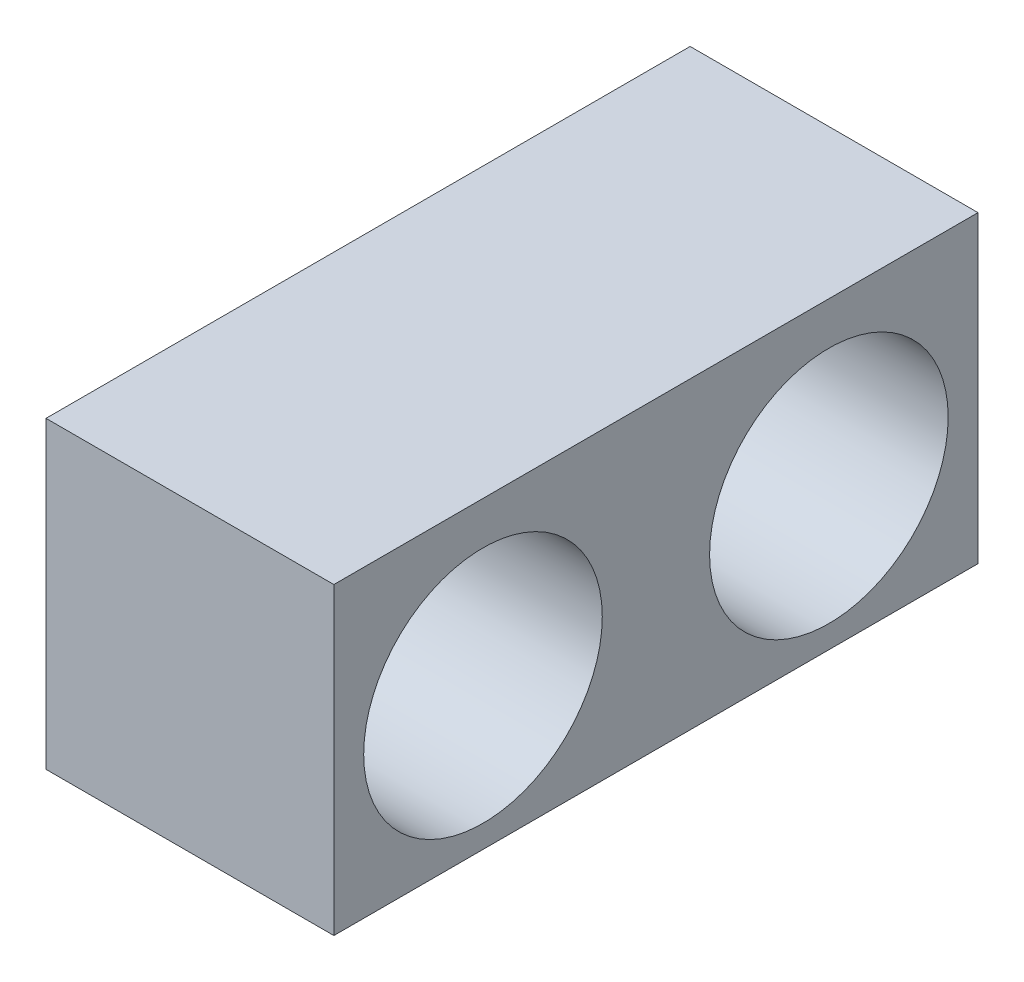
SolidWorks part; units mm, degrees
ref_plane "Front Plane" through (0, 0, 0) normal (0, 0, 1) x (1, 0, 0)
ref_plane "Top Plane" through (0, 0, 0) normal (0, 1, 0) x (1, 0, 0)
ref_plane "Right Plane" through (0, 0, 0) normal (1, 0, 0) x (0, 0, -1)
other "Lead Shot"
sketch "Sketch1" plane through (0, 0, 0) normal (0, 1, 0) x (1, 0, 0)
  circle A0 centre (0, 0) radius 75
  dimension "D1" = 150
extrude "Boss-Extrude1" add sketch "Sketch1" along normal blind 100
sketch "Sketch2" plane through (0, 100, 0) normal (0, 1, 0) x (1, 0, 0)
  line L1 (-22.2, -49.6757) -> (-22.2, 49.6757) construction
  line L3 (-22.2, -49.6757) -> (-22.2, 49.6757)
  line L4 (22.2, 49.6757) -> (22.2, -49.6757) construction
  line L5 (22.2, 49.6757) -> (22.2, -49.6757)
  line L6 (-22.2, -49.6757) -> (22.2, -49.6757)
  line L7 (-22.2, 49.6757) -> (22.2, 49.6757)
extrude "Cut-Extrude1" cut sketch "Sketch2" against normal through all flip side to cut
sketch "Sketch3" plane through (0, 0, 49.6757) normal (0, 0, 1) x (1, 0, 0)
  line L0 (-28.2, 46.8908) -> (-22.2, 46.8908) construction
  line L1 (-28.2, 46.8908) -> (-22.2, 46.8908) construction
  line L3 (-22.2, 46.8908) -> (22.2, 46.8908)
  line L4 (-22.2, 46.8908) -> (-22.2, 100)
  line L5 (-22.2, 100) -> (22.2, 100)
  line L6 (22.2, 46.8908) -> (22.2, 100)
extrude "Cut-Extrude2" cut sketch "Sketch3" against normal through all
sketch "Sketch4" plane through (-22.2, 0, 0) normal (-1, 0, 0) x (0, 0, 1)
  circle A0 centre (26.6757, 21.8908) radius 18.4 construction
  circle A1 centre (-26.6757, 21.8908) radius 18.4 construction
  circle A2 centre (26.6757, 21.8908) radius 18.4
  circle A3 centre (-26.6757, 21.8908) radius 18.4
extrude "Cut-Extrude3" cut sketch "Sketch4" against normal through all
